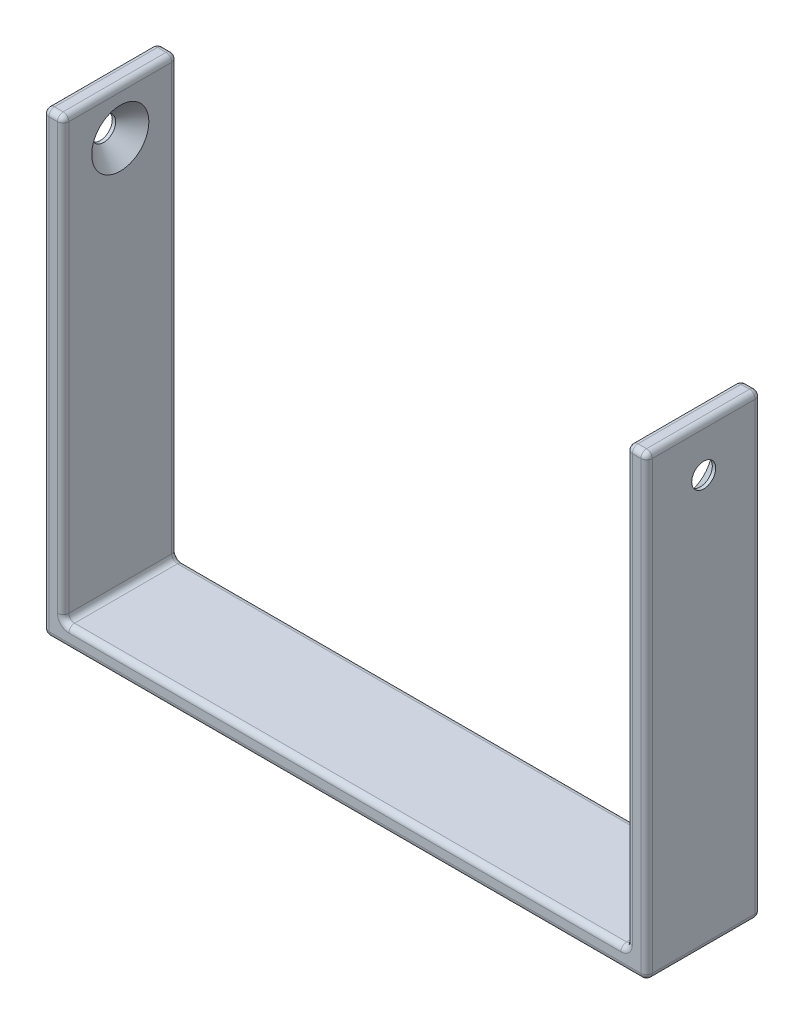
SolidWorks part; units mm, degrees
material "ABS"
ref_plane "Front Plane" through (0, 0, 0) normal (0, 0, 1) x (1, 0, 0)
ref_plane "Top Plane" through (0, 0, 0) normal (0, 1, 0) x (1, 0, 0)
ref_plane "Right Plane" through (0, 0, 0) normal (1, 0, 0) x (0, 0, -1)
sketch "Sketch1" plane through (0, 0, 0) normal (1, 0, 0) x (0, 0, -1)
  line L1 (-10, 80) -> (10, 80)
  line L2 (-10, 80) -> (-10, 0)
  line L3 (-10, 0) -> (10, 0)
  line L4 (10, 80) -> (10, 0)
  point P4 (0, 0)
  dimension "D1" = 20
  dimension "D2" = 80
extrude "Boss-Extrude1" add sketch "Sketch1" against normal blind 105.6
sketch "Sketch2" plane through (0, 0, -10) normal (0, 0, -1) x (-1, 0, 0)
  line L0 (105.6, 80) -> (0, 80) construction
  line L1 (3.5, 80) -> (102.1, 80)
  line L2 (3.5, 80) -> (3.5, 3.5)
  line L3 (3.5, 3.5) -> (102.1, 3.5)
  line L4 (102.1, 80) -> (102.1, 3.5)
  point P4 (52.8, 80)
  dimension "D1" = 76.5
  dimension "D2" = 98.6
extrude "Cut-Extrude1" cut sketch "Sketch2" against normal up to next
hole_wizard "M5 Tapped Hole2" positions "Sketch3" profile "Sketch4" tap size "M5" standard "DIN" end condition up to next
sketch "Sketch3" plane through (-102.1, 0, 0) normal (1, 0, 0) x (0, 0, -1)
  line L0 (-10, 80) -> (10, 80) construction
  line L1 (10, 3.5) -> (10, 80) construction
  point P0 (0, 72)
sketch "Sketch4" plane through (-102.1, 72, 0) normal (0, 1, 0) x (0, 0, -1)
  line L0 (0, 0) -> (0, 3.5)
  line L1 (0, 3.5) -> (2.1, 3.5)
  line L2 (2.1, 3.5) -> (2.1, 2.9)
  line L3 (2.1, 2.9) -> (5, 0)
  line L5 (5, 0) -> (0, 0)
  line L6 (-2.1, 2.9) -> (-5, 0) construction
  line L11 (0, -6.35) -> (0, 107.95) construction
  dimension "Thru Tap Drill Dia." = 4.2
  dimension "Thru Tap Drill Depth" = 3.5
  dimension "Near C'Sink Dia." = 10
  dimension "Near C'Sink Angle" = 90
cosmetic thread "Hole Thread2" parameters "D2"=5
hole_wizard "M5 Tapped Hole1" positions "Sketch13" profile "Sketch15" tap size "M5" standard "DIN" end condition up to next
sketch "Sketch13" plane through (-3.5, 0, 0) normal (-1, 0, 0) x (0, 0, 1)
  line L0 (10, 80) -> (10, 3.5) construction
  line L1 (10, 80) -> (-10, 80) construction
  point P0 (0, 72)
sketch "Sketch15" plane through (-3.5, 72, 0) normal (0, 1, 0) x (0, 0, 1)
  line L0 (0, 0) -> (0, 3.5)
  line L1 (0, 3.5) -> (2.1, 3.5)
  line L2 (2.1, 3.5) -> (2.1, 2.9)
  line L3 (2.1, 2.9) -> (5, 0)
  line L5 (5, 0) -> (0, 0)
  line L6 (-2.1, 2.9) -> (-5, 0) construction
  line L11 (0, -6.35) -> (0, 107.95) construction
  dimension "Thru Tap Drill Dia." = 4.2
  dimension "Thru Tap Drill Depth" = 3.5
  dimension "Near C'Sink Dia." = 10
  dimension "Near C'Sink Angle" = 90
cosmetic thread "Hole Thread1" parameters "D2"=5
fillet "Fillet1" radius 1 24 edges at (-103.85, 80, 10) (-105.6, 80, 0) (-103.85, 80, -10) (-102.1, 80, 0) (-1.75, 80, -10) (0, 80, 0) (-1.75, 80, 10) (-3.5, 80, 0) (-52.8, 3.5, 10) (-52.8, 3.5, -10) (-3.5, 41.75, 10) (-3.5, 3.5, 0) (-3.5, 41.75, -10) (-102.1, 41.75, 10) (-102.1, 41.75, -10) (-102.1, 3.5, 0) (0, 40, 10) (0, 40, -10) (-105.6, 40, 10) (-105.6, 40, -10) (-52.8, 0, -10) (-105.6, 0, 0) (-52.8, 0, 10) (0, 0, 0)
equation "\"D1@Sketch1\" = \"Ubar_W_nominal\""
equation "\"D2@Sketch1\" = \"Ubar_L_nominal\""
equation "\"D1@Boss-Extrude1\" = \"Ubar_T_bottom\""
equation "\"D1@Sketch2\"=\"Ubar_L_nominal\"-\"Ubar_T_nominal\""
equation "\"D2@Sketch2\"= \"Ubar_T_bottom\" - ( \"Ubar_T_nominal\" * 2 )"
equation "\"D1@Sketch3\"=0.008"
equation "\"D2@Sketch3\" = \"Ubar_W_nominal\" / 2"
equation "\"Ubar_W_nominal\"= 0.0200m"
equation "\"Ubar_T_nominal\"= 0.0035m"
equation "\"Ubar_T_bottom\"= 0.1056m"
equation "\"Ubar_L_nominal\"= 0.0800m"
equation "\"D1@Sketch13\"=\"Ubar_W_nominal\"/2"
equation "\"D2@Sketch13\"=0.008"
